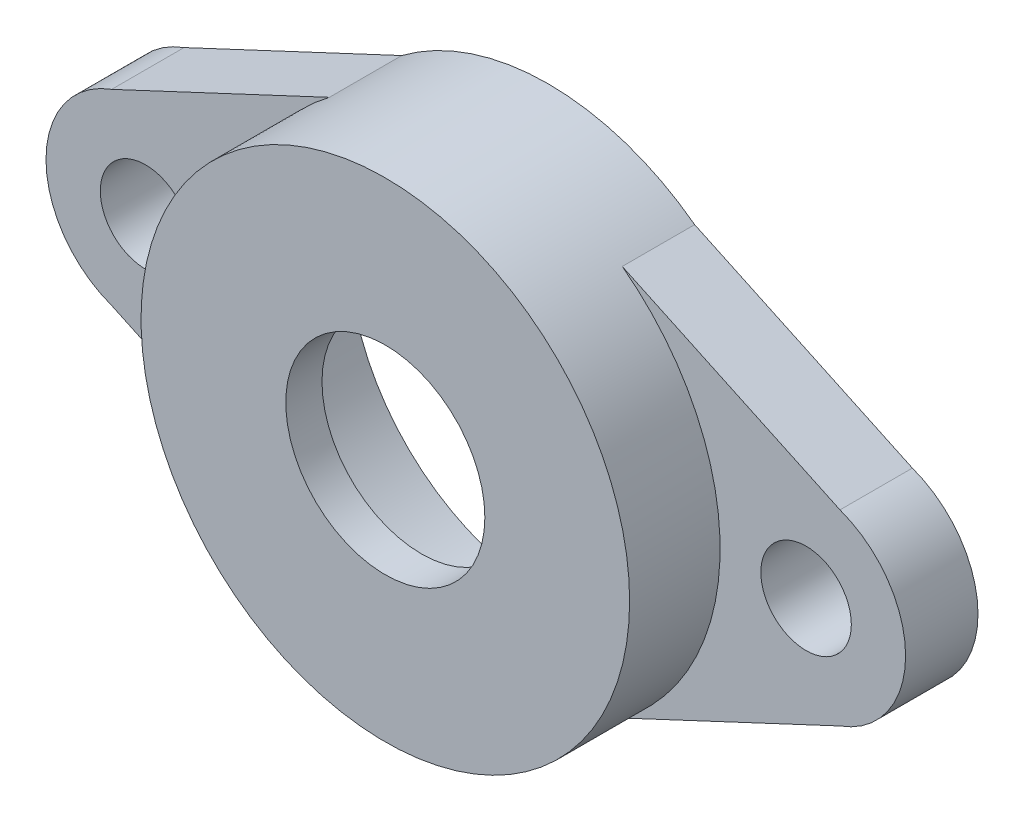
SolidWorks part; units mm, degrees
material "Cast Alloy Steel"
ref_plane "Plano frontal" through (0, 0, 0) normal (0, 0, 1) x (1, 0, 0)
ref_plane "Plano superior" through (0, 0, 0) normal (0, 1, 0) x (1, 0, 0)
ref_plane "Plano direito" through (0, 0, 0) normal (1, 0, 0) x (0, 0, -1)
sketch "Esboço1" plane through (0, 0, 0) normal (0, 0, 1) x (1, 0, 0)
  line L0 (-18.25, 0) -> (18.25, 0) construction
  line L1 (0, 0) -> (0, 13.5) construction
  line L2 (-20.124, 5.1709) -> (-8.0937, 10.8047)
  line L3 (-18.25, 0) -> (-23.75, 0) construction
  line L4 (-20.124, -5.1709) -> (-8.0937, -10.8047)
  line L5 (20.124, -5.1709) -> (8.0937, -10.8047)
  line L6 (20.124, 5.1709) -> (8.0937, 10.8047)
  circle A0 centre (0, 0) radius 4
  circle A1 centre (-18.25, 0) radius 2.5
  circle A2 centre (18.25, 0) radius 2.5
  arc A4 (-20.124, 5.1709) -> (-20.124, -5.1709) centre (-18.25, 0) ccw
  arc A5 (8.0937, 10.8047) -> (-8.0937, 10.8047) centre (0, 0) ccw
  arc A6 (8.0937, -10.8047) -> (-8.0937, -10.8047) centre (0, 0) cw
  arc A7 (20.124, 5.1709) -> (20.124, -5.1709) centre (18.25, 0) cw
  dimension "D1" = 5
  dimension "D2" = 5
  dimension "D4" = 8
  dimension "D6" = 11
  dimension "D3" = 36.5
extrude "Ressalto-extrusão1" add sketch "Esboço1" along normal blind 4
sketch "Esboço2" plane through (0, 0, 4) normal (0, 0, 1) x (1, 0, 0)
  circle A0 centre (0, 0) radius 12.0157
  circle A1 centre (0, 0) radius 10.4838
extrude "Ressalto-extrusão2" add sketch "Esboço2" along normal blind 5
sketch "Esboço3" plane through (0, 0, 4) normal (0, 0, 1) x (1, 0, 0)
  circle A0 centre (0, 0) radius 4
  circle A1 centre (0, 0) radius 5.5
  dimension "D1" = 11
extrude "Ressalto-extrusão3" add sketch "Esboço3" along normal blind 9
sketch "Sketch1" plane through (0, 0, 9) normal (0, 0, 1) x (1, 0, 0)
  circle A0 centre (0, 0) radius 13.5
  arc A1 (8.0937, 10.8047) -> (-8.0937, 10.8047) centre (0, 0) ccw construction
extrude "Boss-Extrude1" add sketch "Sketch1" against normal up to surface (5 mm away) up to face at (12.0157, 0, 4)
sketch "Sketch2" plane through (0, 0, 0) normal (0, 0, -1) x (-1, 0, 0)
  circle A0 centre (0, 0) radius 11
  dimension "D1" = 22
extrude "Cut-Extrude1" cut sketch "Sketch2" against normal blind 7
sketch "Sketch3" plane through (0, 0, 13) normal (0, 0, 1) x (1, 0, 0)
  circle A1 centre (0, 0) radius 5.5
  circle A2 centre (0, 0) radius 5.5
  dimension "D1" = 0
extrude "Cut-Extrude2" cut sketch "Sketch3" against normal blind 7
